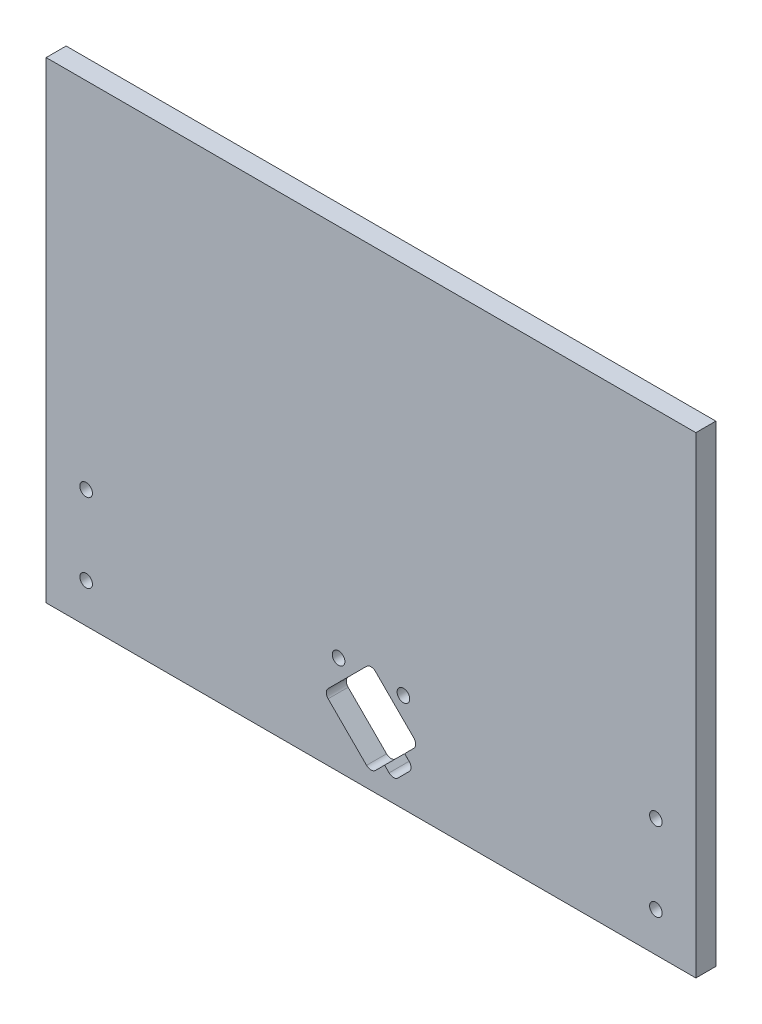
SolidWorks part; units mm, degrees
ref_plane "Front Plane" through (0, 0, 0) normal (0, 0, 1) x (1, 0, 0)
ref_plane "Top Plane" through (0, 0, 0) normal (0, 1, 0) x (1, 0, 0)
ref_plane "Right Plane" through (0, 0, 0) normal (1, 0, 0) x (0, 0, -1)
sketch "Sketch1" plane through (0, 0, 0) normal (0, 0, 1) x (1, 0, 0)
  line L0 (0, -150) -> (0, 150) construction
  line L1 (187.3, -150) -> (-187.3, -150)
  line L2 (187.3, -150) -> (187.3, 150) construction
  line L3 (187.3, 150) -> (-187.3, 150)
  line L4 (-187.3, -150) -> (-187.3, 150) construction
  line L5 (187.3, -150) -> (-187.3, 150) construction
  line L6 (187.3, 150) -> (-187.3, -150) construction
  line L7 (-206.35, -140) -> (206.35, -140) construction
  line L8 (206.35, -150) -> (-206.35, -150)
  line L9 (206.35, -150) -> (206.35, 150)
  line L10 (206.35, 150) -> (-206.35, 150)
  line L11 (-206.35, -150) -> (-206.35, 150)
  line L12 (206.35, -150) -> (-206.35, 150) construction
  line L13 (206.35, 150) -> (-206.35, -150) construction
  line L14 (8.6621, -131.7563) -> (14.3189, -137.4131)
  line L15 (14.3189, -137.4131) -> (20.6829, -131.0492) construction
  line L16 (20.6829, -131.0492) -> (15.026, -125.3923) construction
  line L17 (14.3189, -137.4131) -> (8.6621, -131.7563)
  line L18 (27.0468, -124.6852) -> (14.3189, -137.4131)
  line L19 (21.39, -119.0283) -> (27.0468, -124.6852)
  circle A0 centre (-20.5901, -87.4664) radius 4
  circle A1 centre (20.5901, -87.4664) radius 4
  circle A2 centre (0, -110.3663) radius 5
  point P0 (0, 0)
  point P8 (0, 0)
  line B0 (0, 149.9352) -> (0, -150.0648) construction
  line B1 (-21.9118, -110.3663) -> (21.9118, -110.3663) construction
  line B2 (-15.026, -95.3403) -> (15.026, -125.3923) construction
  line B3 (-30.052, -110.3663) -> (0, -140.4183)
  line B4 (0, -140.4183) -> (30.052, -110.3663) construction
  line B5 (-30.052, -110.3663) -> (30.052, -110.3663) construction
  line B6 (0, -140.4183) -> (0, -80.3142) construction
  line B7 (8.6621, -131.7563) -> (14.3189, -137.4131)
  line B8 (0, -140.4183) -> (8.6621, -131.7563)
  line B9 (-4.9282, -86.0188) -> (-24.3474, -105.4381)
  line B10 (-24.3474, -115.2945) -> (-4.9282, -134.7137)
  line B11 (4.9282, -134.7137) -> (24.3474, -115.2945)
  line B12 (24.3474, -105.4381) -> (4.9282, -86.0188)
  circle B13 centre (0, -132.2781) radius 1.5541
  arc B14 (4.9282, -86.0188) -> (-4.9282, -86.0188) centre (0, -110.3663) ccw
  arc B15 (-24.3474, -105.4381) -> (-24.3474, -115.2945) centre (0, -110.3663) ccw
  arc B16 (-4.9282, -134.7137) -> (4.9282, -134.7137) centre (0, -110.3663) ccw
  arc B17 (24.3474, -115.2945) -> (24.3474, -105.4381) centre (0, -110.3663) ccw
  circle B18 centre (0, -110.3663) radius 13.462
  circle B19 centre (21.9118, -110.3663) radius 1.5541
  circle B20 centre (0, -88.4545) radius 1.5541
  circle B21 centre (-21.9118, -110.3663) radius 1.5541
  line B22 (-31.9435, -112.6113) -> (-27.4534, -108.1212) construction
  line B23 (-27.4534, -108.1212) -> (4.4901, -140.0648) construction
  line B24 (-4.4901, -140.0648) -> (-31.9435, -112.6113) construction
  line B25 (-4.4901, -140.0648) -> (27.4534, -108.1212) construction
  line B26 (27.4534, -108.1212) -> (31.9435, -112.6113) construction
  line B27 (31.9435, -112.6113) -> (4.4901, -140.0648) construction
  line B28 (-27.4534, -108.1212) -> (-27.4534, -80.6678) construction
  line B29 (-27.4534, -80.6678) -> (27.4534, -80.6678) construction
  line B30 (27.4534, -108.1212) -> (27.4534, -80.6678) construction
  circle B31 centre (20.5901, -87.5311) radius 4 construction
  circle B32 centre (-20.5901, -87.5311) radius 4 construction
  circle B33 centre (0, -110.3663) radius 13.462 construction
  circle B34 centre (-21.9118, -110.3663) radius 1.5541 construction
  circle B35 centre (0, -132.2781) radius 1.5541 construction
  circle B36 centre (21.9118, -110.3663) radius 1.5541 construction
  circle B37 centre (0, -88.4545) radius 1.5541 construction
  line B38 (-30.052, -110.3663) -> (0, -80.3142)
  line B39 (0, -80.3142) -> (30.052, -110.3663)
  line B40 (30.052, -110.3663) -> (0, -140.4183)
  dimension "D5" = 8
  dimension "D9" = 10
  dimension "D1" = 374.6
  dimension "D2" = 19.05
  dimension "D3" = 10
  dimension "D4" = 300
  dimension "D6" = 20.5901
  dimension "D7" = 20.5901
  dimension "D8" = 87.4664
sketch_block_instance "Block2-1"
sketch_block "Block2" parameters "D1"=42.5, "D2"=8
sketch_block_instance "nema 17 mount dxf-3"
sketch_block "nema 17 mount dxf"
sketch_block_instance "Fold pattern - Angle Mount v3-3"
sketch_block "Fold pattern - Angle Mount v3"
extrude "Boss-Extrude2" add sketch "Sketch1" along normal blind 12.7
sketch "Sketch2" plane through (0, 0, 12.7) normal (0, 0, 1) x (1, 0, 0)
  line B0 (-206.35, -50) -> (-206.35, -150) construction
  line B1 (-180.95, -50) -> (-180.95, -150) construction
  line B2 (-206.35, -150) -> (-155.55, -150) construction
  line B3 (-206.35, -150) -> (-206.35, -50) construction
  line B4 (-206.35, -50) -> (-155.55, -50) construction
  line B5 (-155.55, -150) -> (-155.55, -50) construction
  line B6 (-206.35, -100) -> (-155.55, -100) construction
  line B7 (0, -50) -> (0, -150) construction
  line B8 (206.35, -100) -> (155.55, -100) construction
  line B9 (155.55, -150) -> (155.55, -50) construction
  line B10 (206.35, -50) -> (155.55, -50) construction
  line B11 (206.35, -150) -> (206.35, -50) construction
  line B12 (206.35, -150) -> (155.55, -150) construction
  line B13 (180.95, -50) -> (180.95, -150) construction
  line B14 (206.35, -50) -> (206.35, -150) construction
  circle B15 centre (-180.95, -75) radius 4
  circle B16 centre (-180.95, -125) radius 4
  circle B17 centre (180.95, -125) radius 4
  circle B18 centre (180.95, -75) radius 4
sketch_block_instance "Block1-1"
sketch_block "Block1"
extrude "Cut-Extrude1" cut sketch "Sketch2" against normal up to next
fillet "Fillet1" radius 4 6 edges at (14.3189, -137.4131, 6.35) (27.0468, -124.6852, 6.35) (0, -140.4183, 6.35) (30.052, -110.3663, 6.35) (0, -80.3142, 6.35) (-30.052, -110.3663, 6.35)
